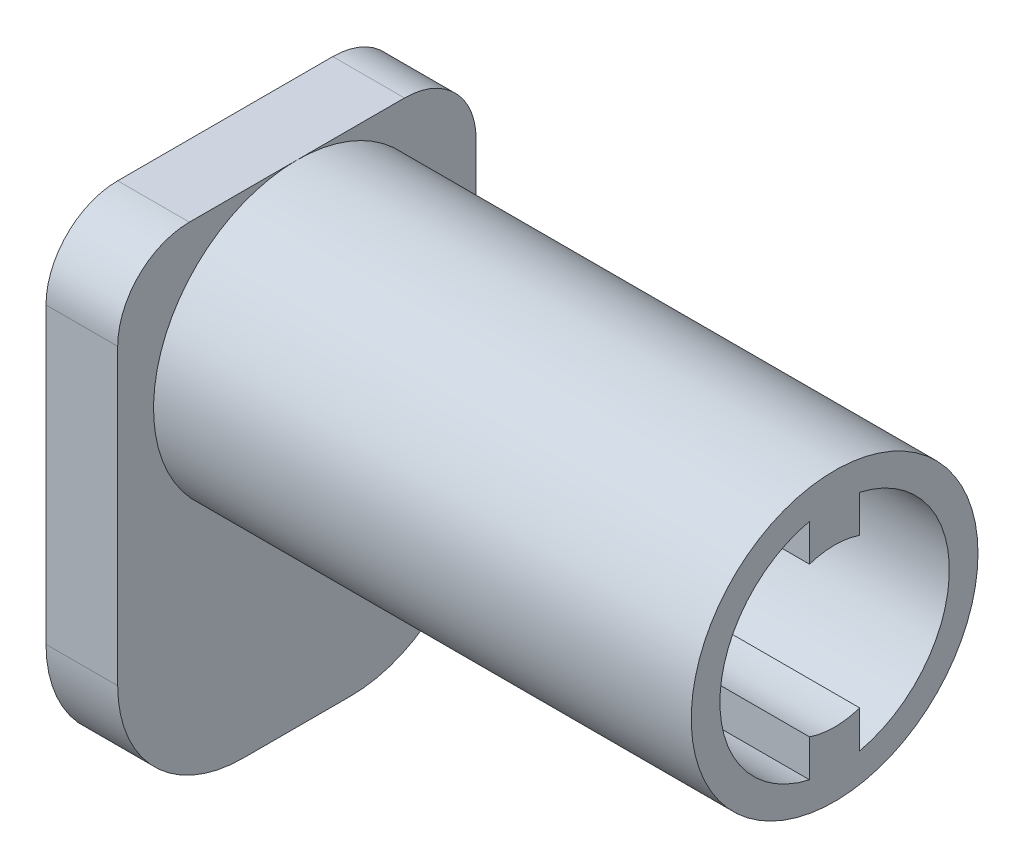
SolidWorks part; units mm, degrees
ref_plane "Front Plane" through (0, 0, 0) normal (0, 0, 1) x (1, 0, 0)
ref_plane "Top Plane" through (0, 0, 0) normal (0, 1, 0) x (1, 0, 0)
ref_plane "Right Plane" through (0, 0, 0) normal (1, 0, 0) x (0, 0, -1)
sketch "Sketch2" plane through (0, 0, 0) normal (1, 0, 0) x (0, 0, -1)
  circle A0 centre (0, 0) radius 4
  dimension "D1" = 8
extrude "Boss-Extrude1" add sketch "Sketch2" against normal blind 15
sketch "Sketch3" plane through (-15, 0, 0) normal (-1, 0, 0) x (0, 0, 1)
  line L0 (0, 0) -> (0, -9.7) construction
  line L1 (-5, 4) -> (5, 4)
  line L2 (-5, 4) -> (-5, -9.7)
  line L3 (-5, -9.7) -> (5, -9.7)
  line L4 (5, 4) -> (5, -9.7)
  dimension "D1" = 9.7
  dimension "D2" = 4
  dimension "D3" = 10
extrude "Boss-Extrude2" add sketch "Sketch3" along normal blind 2
sketch "Sketch4" plane through (0, 0, 0) normal (1, 0, 0) x (0, 0, -1)
  circle A0 centre (0, 0) radius 3.2
  dimension "D1" = 6.4
extrude "Cut-Extrude1" cut sketch "Sketch4" against normal up to surface (15 mm away) up to face at (-15, -1.2333, -0.6667)
sketch "Sketch6" plane through (-17, 0, 0) normal (-1, 0, 0) x (0, 0, 1)
  line L6 (0.7, -2.8618) -> (0.7, -1.7861)
  line L7 (0.7, -2.8618) -> (0.7, -2.0857)
  line L8 (-0.7, -2.8618) -> (0.7, -2.8618) construction
  line L9 (-0.7, -1.7861) -> (-0.7, -2.8618)
  line L10 (-0.7, -2.0857) -> (-0.7, -2.8618)
  line L12 (0, 0) -> (5, 0) construction
  line L13 (5, -9.7) -> (5, 4) construction
  line L15 (-0.7, 2.0857) -> (-0.7, 2.8618)
  line L16 (-0.7, 2.8618) -> (0.7, 2.8618) construction
  line L17 (0.7, 2.8618) -> (0.7, 2.0857)
  line L18 (-0.7, -2.8618) -> (-0.7, -3.1225)
  line L19 (0.7, -2.8618) -> (0.7, -3.1225)
  line L20 (-0.7, 2.8618) -> (-0.7, 3.1225)
  line L21 (0.7, 2.8618) -> (0.7, 3.1225)
  arc A1 (-0.7, 2.0857) -> (0.7, 2.0857) centre (0, 0) cw
  arc A2 (-0.99, -1.9647) -> (0.99, -1.9647) centre (0, 0) ccw
  arc A3 (-0.7, -2.0857) -> (0.7, -2.0857) centre (0, 0) ccw
  circle A4 centre (0, 0) radius 3.2 construction
  arc A5 (-0.7, -3.1225) -> (0.7, -3.1225) centre (0, 0) ccw
  arc A6 (-0.7, 3.1225) -> (0.7, 3.1225) centre (0, 0) cw
  dimension "D3" = 0.2
  dimension "D1" = 0.2
  dimension "D2" = 0.2
sketch "Sketch7" plane through (-17, 0, 0) normal (-1, 0, 0) x (0, 0, 1)
  circle A0 centre (0, 0) radius 1.6
  dimension "D1" = 3.2
extrude "Cut-Extrude4" cut sketch "Sketch7" against normal through all
extrude "Boss-Extrude3" add sketch "Sketch6" against normal up to surface (17 mm away) up to face at (0, 0, -3.2)
fillet "Fillet2" radius 2 2 edges at (-16, 4, 5) (-16, 4, -5)
fillet "Fillet3" radius 3.5 2 edges at (-16, -9.7, -5) (-16, -9.7, 5)
